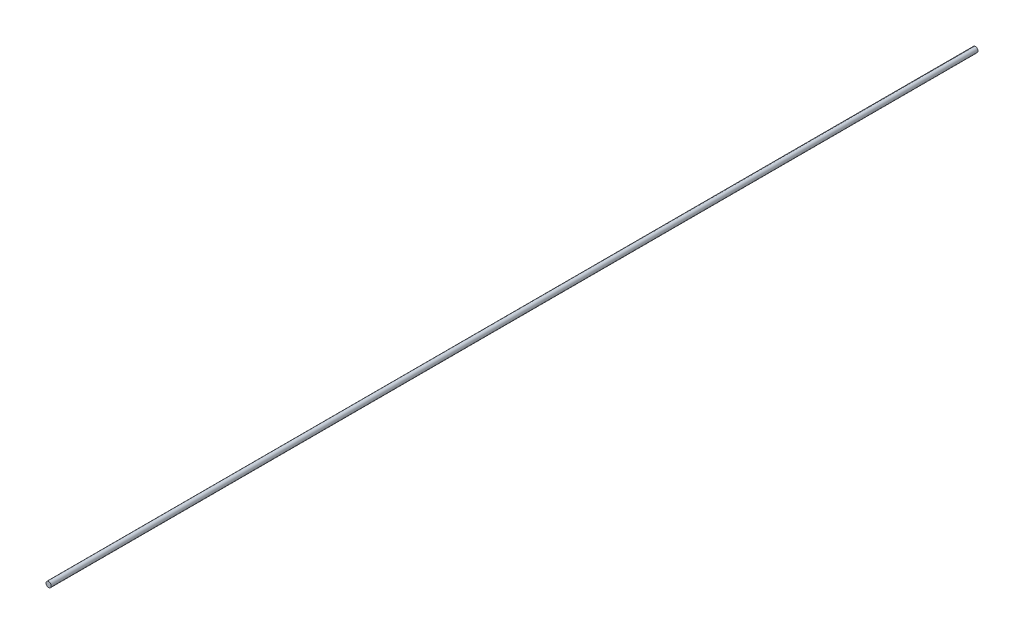
SolidWorks part; units mm, degrees
material "6061 Alloy"
ref_plane "Front Plane" through (0, 0, 0) normal (0, 0, 1) x (1, 0, 0)
ref_plane "Top Plane" through (0, 0, 0) normal (0, 1, 0) x (1, 0, 0)
ref_plane "Right Plane" through (0, 0, 0) normal (1, 0, 0) x (0, 0, -1)
sketch "Sketch1" plane through (0, 0, 0) normal (0, 0, 1) x (1, 0, 0)
  circle A0 centre (0, 0) radius 12.7
  dimension "D1" = 25.4
extrude "Boss-Extrude1" add sketch "Sketch1" along normal blind 4491.9636
equation "\"d\"= 1"
equation "\"F\"= 400"
equation "\"defl\"= 0.009"
equation "\"E\"= 10007603.9"
equation "\"A\"= pi * \"d\" * \"d\" / 4"
equation "\"L\"= \"defl\" * \"E\" * \"A\" / \"F\""
equation "\"D1@Sketch1\"=\"d\""
equation "\"D1@Boss-Extrude1\"=\"L\""
